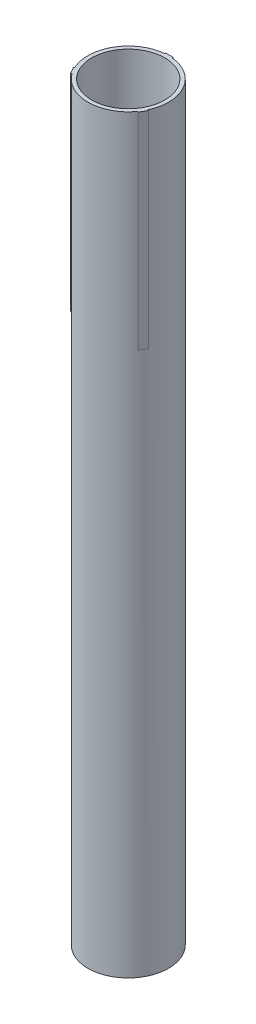
SolidWorks part; units mm, degrees
material "Fibra de Vidro A"
ref_plane "Plano frontal" through (0, 0, 0) normal (0, 0, 1) x (1, 0, 0)
ref_plane "Plano superior" through (0, 0, 0) normal (0, 1, 0) x (1, 0, 0)
ref_plane "Plano direito" through (0, 0, 0) normal (1, 0, 0) x (0, 0, -1)
sketch "Esboço1" plane through (0, 0, 0) normal (0, 1, 0) x (1, 0, 0)
  circle A0 centre (0, 0) radius 21.5
  circle A1 centre (0, 0) radius 19.5
  dimension "D1" = 43
  dimension "D2" = 39
extrude "Ressalto-extrusão1" add sketch "Esboço1" along normal blind 400
sketch "Esboço2" plane through (0, 400, 0) normal (0, 1, 0) x (1, 0, 0)
  line L4 (2, 21.9305) -> (2, 21.2349)
  line L5 (2, 21.9305) -> (-1.9989, 21.9305)
  line L6 (-1.9989, 21.9305) -> (-1.9989, 21.2349)
  line L7 (-1.9989, 21.2349) -> (0, 21.5)
  line L8 (0, 21.5) -> (2, 21.2349)
  circle A0 centre (0, 0) radius 21.5 construction
extrude "Ressalto-extrusão3" add sketch "Esboço2" against normal blind 110 contours L5 L6 L7 L8 L4
pattern_circular "PadrãoCircular2" count 3 over 360 about axis through (0, 0, 0) along (0, 1, 0) of "Ressalto-extrusão3"
